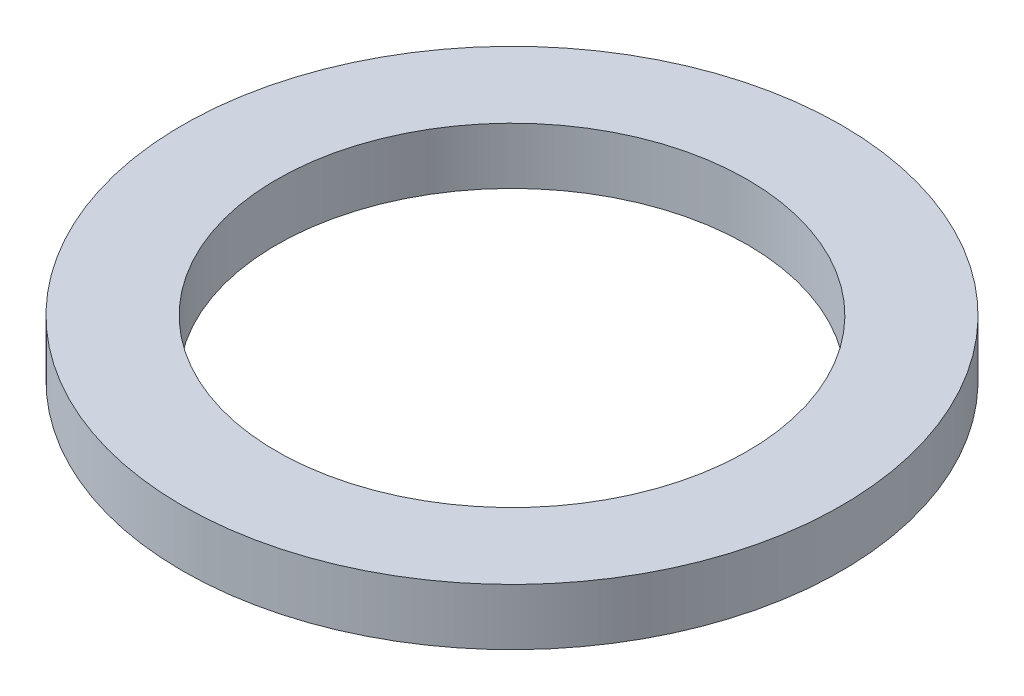
SolidWorks part; units mm, degrees
ref_plane "Front Plane" through (0, 0, 0) normal (0, 0, 1) x (1, 0, 0)
ref_plane "Top Plane" through (0, 0, 0) normal (0, 1, 0) x (1, 0, 0)
ref_plane "Right Plane" through (0, 0, 0) normal (1, 0, 0) x (0, 0, -1)
sketch "Sketch1" plane through (0, 0, 0) normal (0, 1, 0) x (1, 0, 0)
  circle A0 centre (0, 0) radius 22.225
  circle A1 centre (0, 0) radius 15.875
  dimension "D1" = 44.45
  dimension "D2" = 31.75
extrude "Boss-Extrude1" add sketch "Sketch1" along normal blind 3.81
